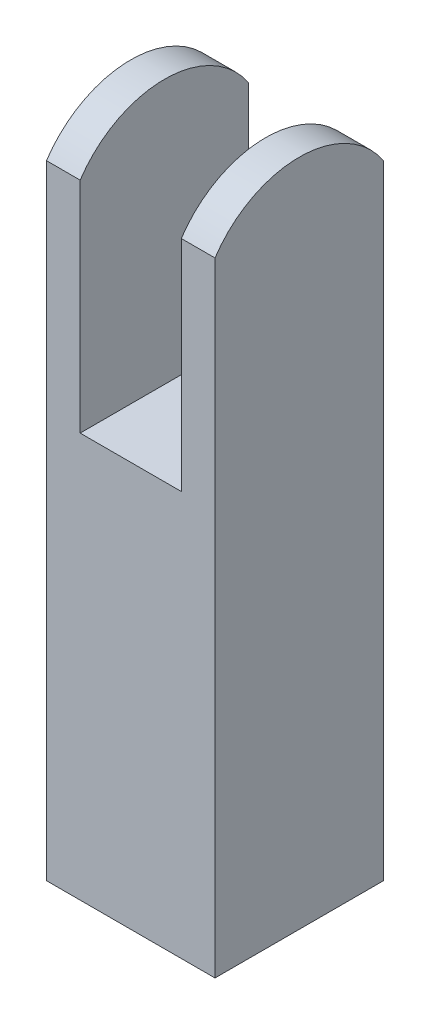
SolidWorks part; units mm, degrees
ref_plane "Front Plane" through (0, 0, 0) normal (0, 0, 1) x (1, 0, 0)
ref_plane "Top Plane" through (0, 0, 0) normal (0, 1, 0) x (1, 0, 0)
ref_plane "Right Plane" through (0, 0, 0) normal (1, 0, 0) x (0, 0, -1)
sketch "Sketch1" plane through (0, 0, 0) normal (0, 1, 0) x (1, 0, 0)
  line L1 (0, 0) -> (-50, 0)
  line L2 (0, 0) -> (0, 50)
  line L3 (0, 50) -> (-50, 50)
  line L4 (-50, 0) -> (-50, 50)
  dimension "D1" = 50
  dimension "D2" = 50
extrude "Boss-Extrude1" add sketch "Sketch1" along normal blind 200
sketch "Sketch4" plane through (0, 200, 0) normal (0, 1, 0) x (1, 0, 0)
  line L0 (-50, 0) -> (0, 0) construction
  line L1 (-40, 0) -> (-10, 0)
  line L2 (-40, 0) -> (-40, 50)
  line L3 (-40, 50) -> (-10, 50)
  line L4 (-10, 0) -> (-10, 50)
  line L5 (0, 50) -> (-50, 50) construction
  line L6 (-50, 50) -> (-50, 0) construction
  line L7 (0, 0) -> (0, 50) construction
  dimension "D1" = 10
  dimension "D2" = 10
  dimension "D3" = 50
extrude "Cut-Extrude1" cut sketch "Sketch4" against normal blind 80
sketch "Sketch5" plane through (0, 0, 0) normal (1, 0, 0) x (0, 0, -1)
  line L0 (0, 200) -> (0, 0) construction
  line L1 (50, 200) -> (50, 0) construction
  arc A0 (0, 185) -> (50, 185) centre (25, 168.4169) cw
  dimension "D1" = 15
  dimension "D2" = 15
extrude "Cut-Extrude2" cut sketch "Sketch5" against normal through all and the other way through all
